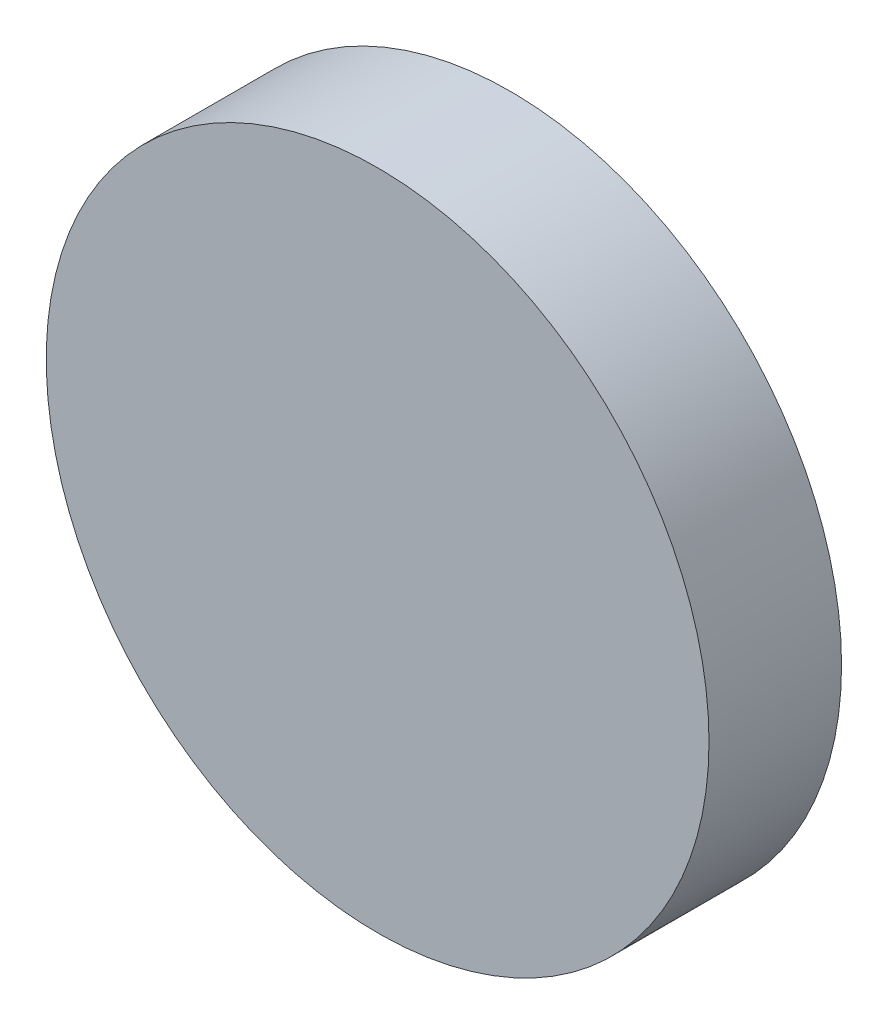
SolidWorks part; units mm, degrees
ref_plane "Alzado" through (0, 0, 0) normal (0, 0, 1) x (1, 0, 0)
ref_plane "Planta" through (0, 0, 0) normal (0, 1, 0) x (1, 0, 0)
ref_plane "Vista lateral" through (0, 0, 0) normal (1, 0, 0) x (0, 0, -1)
sketch "Croquis1" plane through (0, 0, 0) normal (0, 0, 1) x (1, 0, 0)
  circle A0 centre (-108.5046, -77.7492) radius 5
  dimension "D1" = 10
extrude "Saliente-Extruir1" add sketch "Croquis1" along normal blind 2
